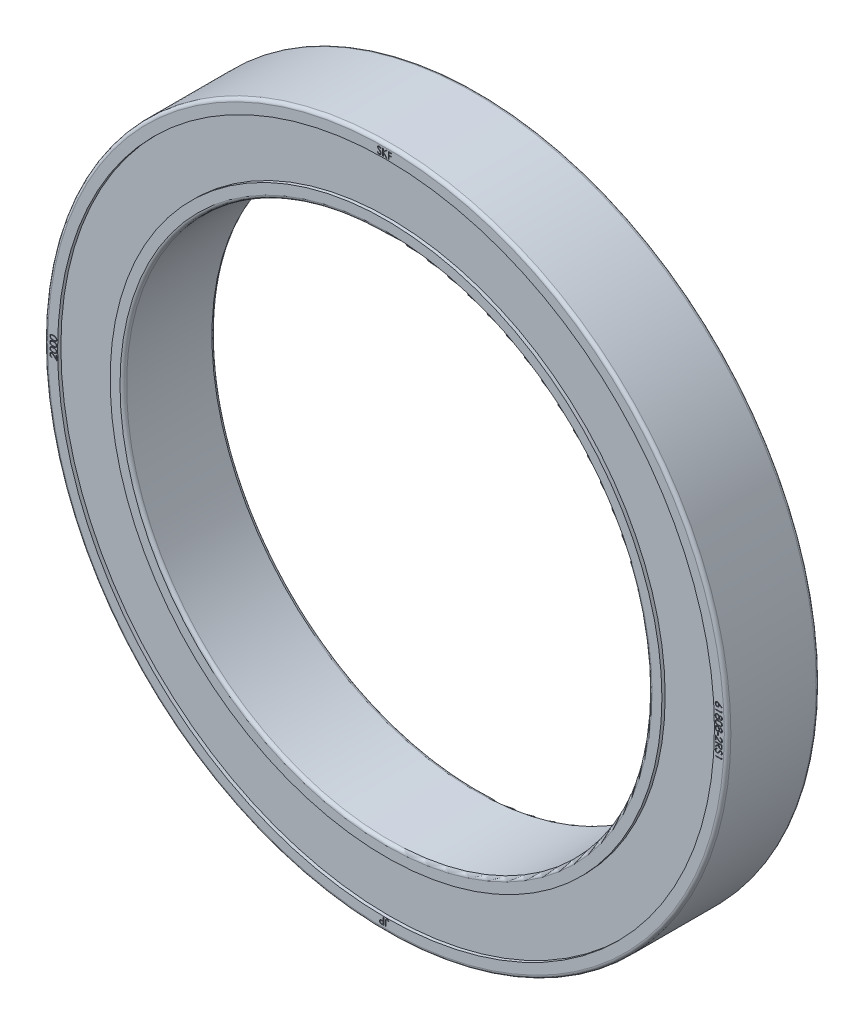
SolidWorks part; units mm, degrees
ref_plane "Front Plane" through (0, 0, 0) normal (0, 0, 1) x (1, 0, 0)
ref_plane "Top Plane" through (0, 0, 0) normal (0, 1, 0) x (1, 0, 0)
ref_plane "Right Plane" through (0, 0, 0) normal (1, 0, 0) x (0, 0, -1)
sketch "Sketch1" plane through (0, 0, 0) normal (0, 0, 1) x (1, 0, 0)
  circle A0 centre (0, 0) radius 26
  circle A1 centre (0, 0) radius 20
  dimension "D1" = 6
extrude "Boss-Extrude1" add sketch "Sketch1" along normal blind 7
sketch "Sketch2" plane through (0, 0, 7) normal (0, 0, 1) x (1, 0, 0)
  circle A0 centre (0, 0) radius 25
  circle A1 centre (0, 0) radius 21
extrude "Cut-Extrude1" cut sketch "Sketch2" against normal blind 0.25
sketch "Sketch3" plane through (0, 0, 0) normal (0, 0, -1) x (-1, 0, 0)
  circle A0 centre (0, 0) radius 25
  circle A1 centre (0, 0) radius 21
extrude "Cut-Extrude2" cut sketch "Sketch3" against normal blind 0.25
fillet "Fillet1" radius 0.25 4 edges at (26, 0, 0) (26, 0, 7) (20, 0, 0) (20, 0, 7)
sketch "Sketch4" plane through (0, 0, 7) normal (0, 0, 1) x (1, 0, 0)
  line L0 (0, 25.75) -> (0, 24.6696) construction
  line L1 (-2.5, 25.0855) -> (2.5, 25.0855) construction
  circle A2 centre (0, 0) radius 25.75 construction
  text T0 "         SKF" font "Century Gothic" height in points 2
  point P0 (0, 25.2098)
extrude "Cut-Extrude3" cut sketch "Sketch4" against normal blind 0.1
sketch "Sketch5" plane through (0, 0, 7) normal (0, 0, 1) x (1, 0, 0)
  line L1 (25.069, 2.5) -> (25.069, -2.5) construction
  text T0 "   61808-2RS1" font "Century Gothic" height in points 2
  point P12 (25.069, 0)
extrude "Cut-Extrude4" cut sketch "Sketch5" against normal blind 0.1
sketch "Sketch6" plane through (0, 0, 7) normal (0, 0, 1) x (1, 0, 0)
  line L0 (0, -25.75) -> (0, -25.0699) construction
  line L1 (0.25, -25.0699) -> (-0.25, -25.0699) construction
  circle A0 centre (0, 0) radius 25.75 construction
  text T0 "JP" font "Century Gothic" height in points 2
  point P9 (0, -25.0699)
extrude "Cut-Extrude5" cut sketch "Sketch6" against normal blind 0.1
sketch "Sketch7" plane through (0, 0, 7) normal (0, 0, 1) x (1, 0, 0)
  line L0 (-25.75, 0) -> (-25.0583, 0) construction
  line L1 (-25.0583, -1.4443) -> (-25.0583, 1.4443) construction
  circle A0 centre (0, 0) radius 25.75 construction
  text T0 "   2000" font "Century Gothic" height in points 2
  point P9 (-25.0583, 0)
extrude "Cut-Extrude6" cut sketch "Sketch7" against normal blind 0.1
